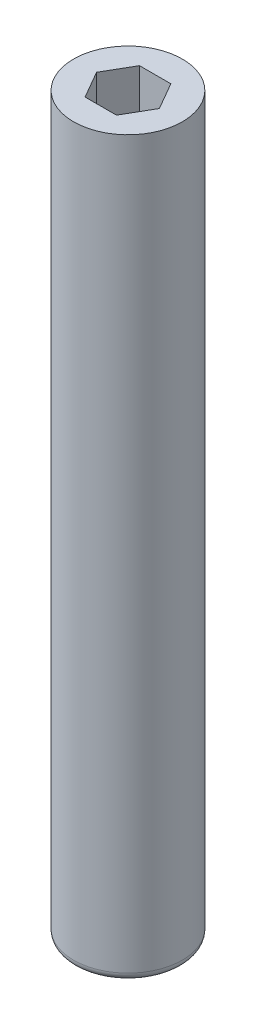
SolidWorks part; units mm, degrees
material "High-leaded brass, UNS C34200"
ref_plane "Front Plane" through (0, 0, 0) normal (0, 0, 1) x (1, 0, 0)
ref_plane "Top Plane" through (0, 0, 0) normal (0, 1, 0) x (1, 0, 0)
ref_plane "Right Plane" through (0, 0, 0) normal (1, 0, 0) x (0, 0, -1)
sketch "Sketch1" plane through (0, 0, 0) normal (0, 1, 0) x (1, 0, 0)
  circle A0 centre (0, 0) radius 5.08
  dimension "D1" = 10.16
extrude "Boss-Extrude1" add sketch "Sketch1" along normal blind 68.58
sketch "Sketch2" plane through (0, 68.58, 0) normal (0, 1, 0) x (1, 0, 0)
  line L1 (-1.4665, -2.54) -> (1.4665, -2.54)
  line L2 (1.4665, -2.54) -> (2.9329, 0)
  line L3 (2.9329, 0) -> (1.4665, 2.54)
  line L4 (1.4665, 2.54) -> (-1.4665, 2.54)
  line L5 (-1.4665, 2.54) -> (-2.9329, 0)
  line L6 (-2.9329, 0) -> (-1.4665, -2.54)
  circle A0 centre (0, 0) radius 2.54 construction
  dimension "D1" = 5.08
extrude "Cut-Extrude1" cut sketch "Sketch2" against normal blind 5.08
fillet "Fillet1" radius 0.762 1 edges at (0, 0, 5.08)
